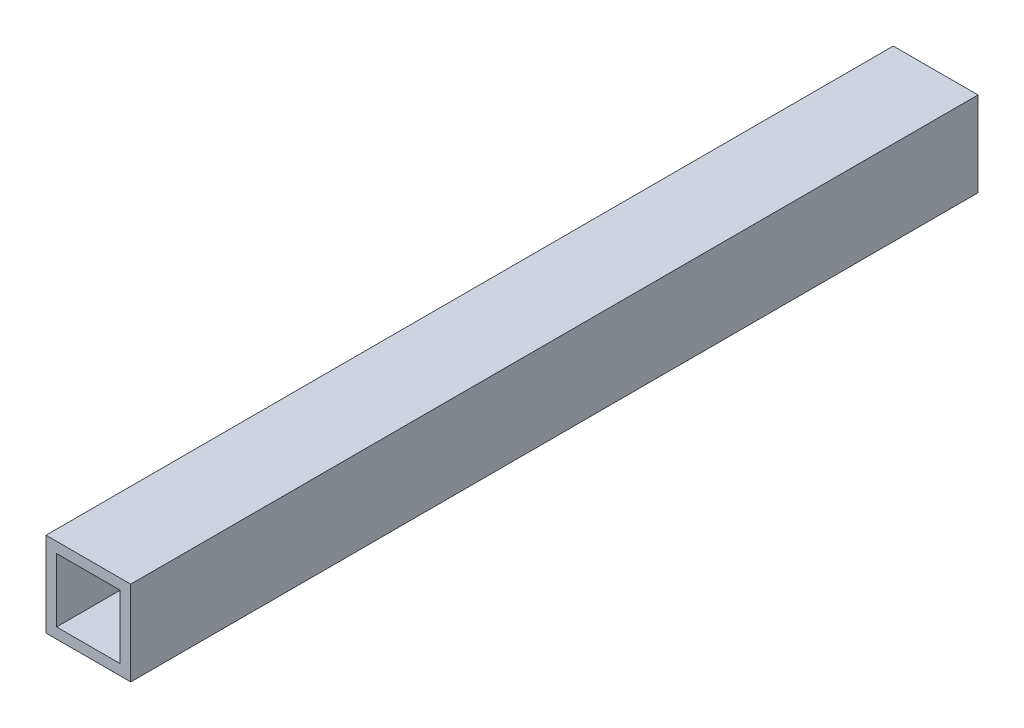
SolidWorks part; units mm, degrees
ref_plane "Front Plane" through (0, 0, 0) normal (0, 0, 1) x (1, 0, 0)
ref_plane "Top Plane" through (0, 0, 0) normal (0, 1, 0) x (1, 0, 0)
ref_plane "Right Plane" through (0, 0, 0) normal (1, 0, 0) x (0, 0, -1)
sketch "Sketch1" plane through (0, 0, 0) normal (0, 0, 1) x (1, 0, 0)
  line L1 (0, 0) -> (25.4, 0)
  line L2 (0, 0) -> (0, -25.4)
  line L3 (0, -25.4) -> (25.4, -25.4)
  line L4 (25.4, 0) -> (25.4, -25.4)
  line L5 (3.175, -3.175) -> (22.225, -3.175)
  line L6 (3.175, -3.175) -> (3.175, -22.225)
  line L7 (3.175, -22.225) -> (22.225, -22.225)
  line L8 (22.225, -3.175) -> (22.225, -22.225)
  dimension "D1" = 25.4
  dimension "D2" = 25.4
  dimension "D3" = 0
  dimension "D4" = 0
  dimension "D5" = 3.175
  dimension "D6" = 3.175
  dimension "D7" = 3.175
  dimension "D8" = 3.175
extrude "Boss-Extrude1" add sketch "Sketch1" along normal blind 254
